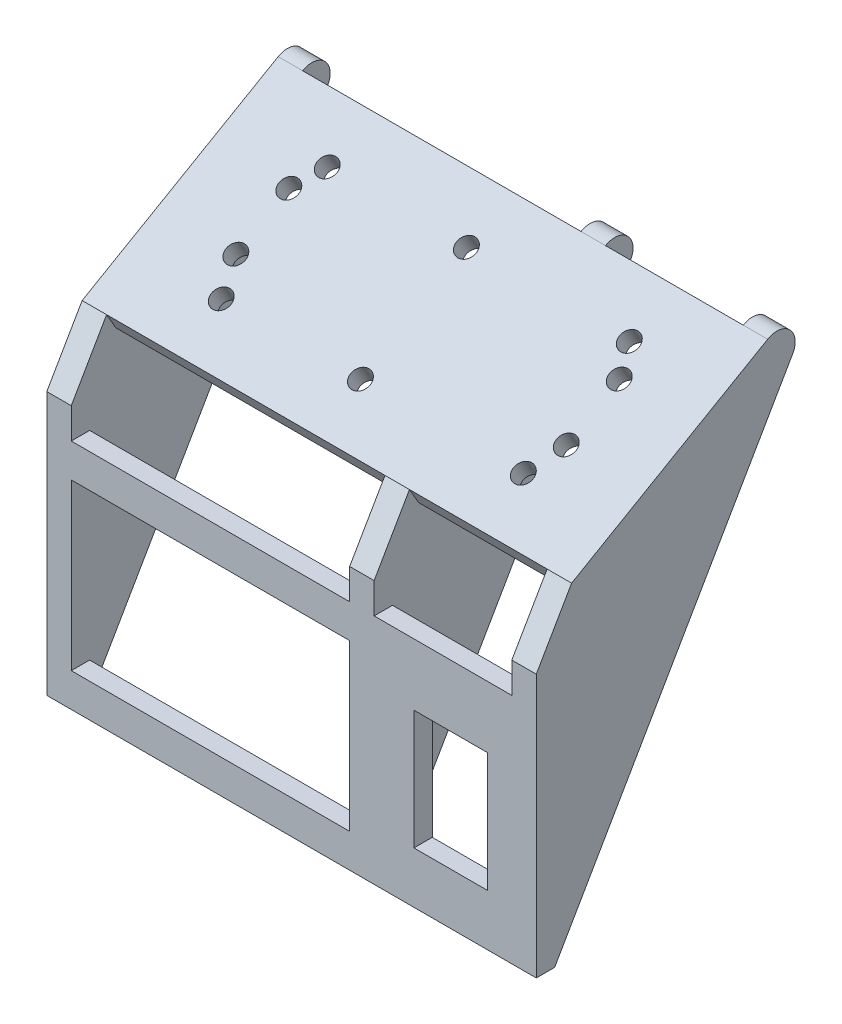
SolidWorks part; units mm, degrees
ref_plane "前视基准面" through (0, 0, 0) normal (0, 0, 1) x (1, 0, 0)
ref_plane "上视基准面" through (0, 0, 0) normal (0, 1, 0) x (1, 0, 0)
ref_plane "右视基准面" through (0, 0, 0) normal (1, 0, 0) x (0, 0, -1)
other "Configuration Table"
sketch "草图1" plane through (0, 0, 0) normal (0, 0, 1) x (1, 0, 0)
  line L1 (-40, 19) -> (40, 19)
  line L2 (-40, 19) -> (-40, -19)
  line L3 (-40, -19) -> (40, -19)
  line L4 (40, 19) -> (40, -19)
  line L5 (-40, 19) -> (40, -19) construction
  line L6 (-40, -19) -> (40, 19) construction
  line L7 (-36, 13.5) -> (9.5, 13.5)
  line L8 (-36, 13.5) -> (-36, -13.5)
  line L9 (-36, -13.5) -> (9.5, -13.5)
  line L10 (9.5, 13.5) -> (9.5, -13.5)
  line L11 (-36, 13.5) -> (9.5, -13.5) construction
  line L12 (-36, -13.5) -> (9.5, 13.5) construction
  line L13 (20, 8.9111) -> (32, 8.9111)
  line L14 (20, 8.9111) -> (20, -10.5889)
  line L15 (20, -10.5889) -> (32, -10.5889)
  line L16 (32, 8.9111) -> (32, -10.5889)
  line L17 (20, 8.9111) -> (32, -10.5889) construction
  line L18 (20, -10.5889) -> (32, 8.9111) construction
  point P0 (0, 0)
  point P6 (-13.25, 0)
  point P12 (26, -0.8389)
  dimension "D1" = 38
  dimension "D2" = 80
  dimension "D3" = 27
  dimension "D4" = 4
  dimension "D5" = 45.5
  dimension "D6" = 19.5
  dimension "D7" = 12
  dimension "D8" = 8
extrude "凸台-拉伸1" add sketch "草图1" along normal blind 3
sketch "草图3" plane through (-40, 0, 0) normal (-1, 0, 0) x (0, 0, 1)
  line L0 (3, 19) -> (3, 24)
  line L1 (3, 24) -> (-2.7735, 34)
  line L2 (-2.7735, 34) -> (-34.8164, 52.5)
  line L4 (-38.9145, 48.4019) -> (0, -19)
  line L5 (0, 19) -> (0, -19) construction
  line L9 (0, 19) -> (0, -19)
  line L10 (0, -19) -> (3, -19)
  line L11 (3, -19) -> (3, 19)
  line L12 (3, 19) -> (0, 19)
  line L13 (0, 19) -> (0, -19)
  line L16 (3, 19) -> (0, 19)
  arc A0 (-38.9145, 48.4019) -> (-34.8164, 52.5) centre (-36.3164, 49.9019) cw
  dimension "D5" = 3
  dimension "D1" = 30
  dimension "D2" = 60
  dimension "D3" = 5
  dimension "D4" = 15
  dimension "D6" = 30
  dimension "D7" = 0
extrude "凸台-拉伸2" add sketch "草图3" against normal up to surface (4 mm away) up to face at (-36, 0, 1.5)
sketch "草图4" plane through (-40, 0, 0) normal (-1, 0, 0) x (0, 0, 1)
  line L5 (-38.9145, 48.4019) -> (0, -19)
  line L6 (0, -19) -> (3, -19)
  line L7 (3, -19) -> (3, 24)
  line L8 (3, 24) -> (-2.7735, 34)
  line L9 (-2.7735, 34) -> (-34.8164, 52.5)
  line L10 (-38.9145, 48.4019) -> (0, -19)
  line L11 (0, -19) -> (3, -19)
  line L12 (3, -19) -> (3, 24)
  line L13 (3, 24) -> (-2.7735, 34)
  line L14 (-2.7735, 34) -> (-34.8164, 52.5)
  arc A1 (-34.8164, 52.5) -> (-38.9145, 48.4019) centre (-36.3164, 49.9019) ccw
  arc A2 (-34.8164, 52.5) -> (-38.9145, 48.4019) centre (-36.3164, 49.9019) ccw
  dimension "D1" = 0
extrude "凸台-拉伸3" add sketch "草图4" along direction (-1, 0, 0) on the side against the normal blind 4 from surface at -49.5 starting at face at (9.5, 0, 1.5)
sketch "草图5" plane through (-40, 0, 0) normal (-1, 0, 0) x (0, 0, 1)
  line L5 (-38.9145, 48.4019) -> (0, -19)
  line L6 (0, -19) -> (3, -19)
  line L7 (3, -19) -> (3, 24)
  line L8 (3, 24) -> (-2.7735, 34)
  line L9 (-2.7735, 34) -> (-34.8164, 52.5)
  line L10 (-38.9145, 48.4019) -> (0, -19)
  line L11 (0, -19) -> (3, -19)
  line L12 (3, -19) -> (3, 24)
  line L13 (3, 24) -> (-2.7735, 34)
  line L14 (-2.7735, 34) -> (-34.8164, 52.5)
  arc A1 (-34.8164, 52.5) -> (-38.9145, 48.4019) centre (-36.3164, 49.9019) ccw
  arc A2 (-34.8164, 52.5) -> (-38.9145, 48.4019) centre (-36.3164, 49.9019) ccw
  dimension "D1" = 0
extrude "凸台-拉伸4" add sketch "草图5" along normal blind 4 from surface at -80 starting at face at (40, 0, 1.5)
sketch "草图6" plane through (0, 24.299, 14.0291) normal (0, 0.866, 0.5) x (1, 0, 0)
  line L1 (-40, 56.4019) -> (40, 56.4019)
  line L2 (-40, 56.4019) -> (-40, 19.4019)
  line L3 (-40, 19.4019) -> (40, 19.4019)
  line L4 (40, 56.4019) -> (40, 19.4019)
extrude "凸台-拉伸5" add sketch "草图6" against normal blind 3
sketch "草图7" plane through (0, 24.299, 14.0291) normal (0, 0.866, 0.5) x (1, 0, 0)
  line L0 (24.75, 56.4019) -> (24.75, 19.4019) construction
  line L1 (-36, 56.4019) -> (9.5, 56.4019) construction
  line L2 (-36, 56.4019) -> (-36, 19.4019) construction
  line L3 (-36, 19.4019) -> (9.5, 19.4019) construction
  line L4 (9.5, 56.4019) -> (9.5, 19.4019) construction
  line L5 (13.5, 56.4019) -> (36, 56.4019) construction
  line L6 (13.5, 56.4019) -> (13.5, 19.4019) construction
  line L7 (13.5, 19.4019) -> (36, 19.4019) construction
  line L8 (36, 56.4019) -> (36, 19.4019) construction
  line L9 (-13.25, 56.4019) -> (-13.25, 19.4019) construction
  line L10 (-24.625, 56.4019) -> (-24.625, 19.4019) construction
  line L11 (-1.89, 56.4019) -> (-1.89, 19.4019) construction
  line L12 (-36, 37.9019) -> (36, 37.9019) construction
  line L13 (0, 86.1974) -> (0, -40.7558) construction
  line L16 (-40, 19.4019) -> (-40, 56.4019) construction
  line L17 (40, 19.4019) -> (40, 56.4019) construction
  circle A0 centre (-24.625, 47.9019) radius 1.6
  circle A1 centre (-1.875, 47.9019) radius 1.6
  circle A2 centre (-1.875, 27.9019) radius 1.6
  circle A3 centre (-24.625, 27.9019) radius 1.6
  circle A4 centre (24.75, 47.9019) radius 1.6
  circle A5 centre (24.75, 27.9019) radius 1.6
  circle A6 centre (-27, 33.4019) radius 1.6
  circle A7 centre (27, 33.4019) radius 1.6
  circle A8 centre (-27, 43.4019) radius 1.6
  circle A9 centre (27, 43.4019) radius 1.6
  dimension "D2" = 3.2
  dimension "D4" = 24.35
  dimension "D5" = 3.2
  dimension "D7" = 3.2
  dimension "D10" = 3.2
  dimension "D11" = 10
  dimension "D1" = 11.36
  dimension "D3" = 10
  dimension "D6" = 10
  dimension "D8" = 54
  dimension "D9" = 14
extrude "切除-拉伸1" cut sketch "草图7" against normal through all contours A0 | A3 | A1 | A2 | A4 | A5 | A6 | A7 | A9 | A8
